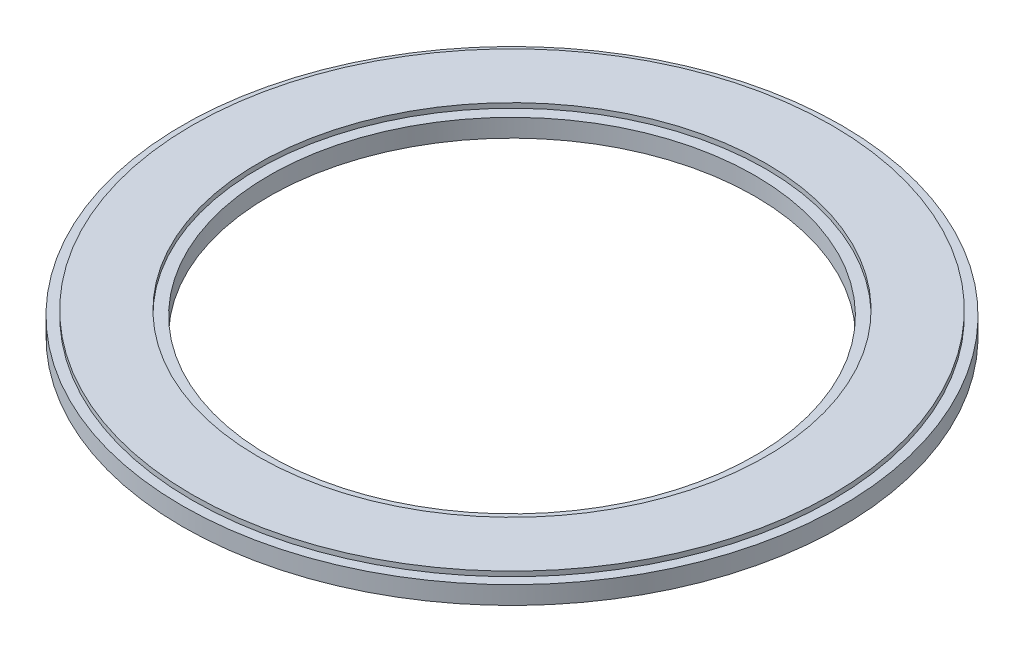
SolidWorks part; units mm, degrees
ref_plane "Ebene vorne" through (0, 0, 0) normal (0, 0, 1) x (1, 0, 0)
ref_plane "Ebene oben" through (0, 0, 0) normal (0, 1, 0) x (1, 0, 0)
ref_plane "Ebene rechts" through (0, 0, 0) normal (1, 0, 0) x (0, 0, -1)
sketch "Skizze1" plane through (0, 0, 0) normal (0, 0, 1) x (1, 0, 0)
  line L0 (0, 0) -> (0, 66200.4677) construction
  line L1 (36.6, 0) -> (46.1, 0)
  line L2 (46.1, 0) -> (46.1, 0.7)
  line L3 (46.1, 0.7) -> (47.5, 0.7)
  line L4 (47.5, 0.7) -> (47.5, 3.3)
  line L5 (47.5, 3.3) -> (46.1, 3.3)
  line L6 (46.1, 3.3) -> (46.1, 4)
  line L7 (46.1, 4) -> (36.6, 4)
  line L8 (36.6, 4) -> (36.6, 3.3)
  line L9 (36.6, 3.3) -> (35, 3.3)
  line L10 (35, 3.3) -> (35, 0.7)
  line L11 (35, 0.7) -> (36.6, 0.7)
  line L12 (36.6, 0.7) -> (36.6, 0)
  point P9 (0, 0)
  dimension "D1" = 70
  dimension "D2" = 95
  dimension "D3" = 4
  dimension "D4" = 2.6
  dimension "D5" = 0.7
  dimension "D6" = 9.5
  dimension "D7" = 1.6
revolve "Rotation1" add sketch "Skizze1" angle 360 about L0
